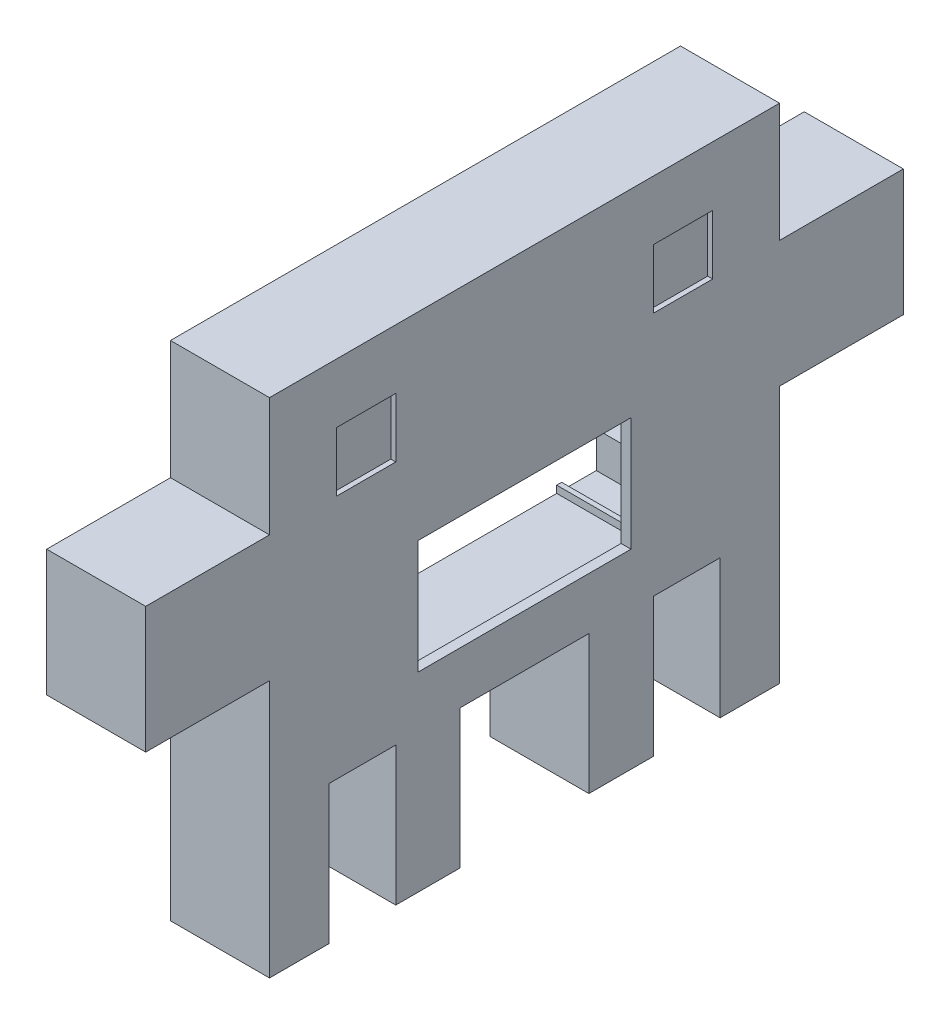
SolidWorks part; units mm, degrees
ref_plane "前视基准面" through (0, 0, 0) normal (0, 0, 1) x (1, 0, 0)
ref_plane "上视基准面" through (0, 0, 0) normal (0, 1, 0) x (1, 0, 0)
ref_plane "右视基准面" through (0, 0, 0) normal (1, 0, 0) x (0, 0, -1)
sketch "草图2" plane through (0, 0, 0) normal (1, 0, 0) x (0, 0, -1)
  line L0 (60.0749, 311.6519) -> (210.0749, 311.6519) construction
  line L1 (109.8601, 259.6877) -> (122.8601, 259.6877)
  line L2 (84.3601, 361.1877) -> (187.3601, 361.1877)
  line L3 (84.3601, 361.1877) -> (84.3601, 337.1877)
  line L4 (84.3601, 259.6877) -> (96.3601, 259.6877)
  line L6 (59.3601, 337.1877) -> (84.3601, 337.1877)
  line L7 (59.3601, 337.1877) -> (59.3601, 311.6877)
  line L8 (59.3601, 311.6877) -> (84.3601, 311.6877)
  line L10 (96.3601, 287.6877) -> (109.8601, 287.6877)
  line L11 (96.3601, 287.6877) -> (96.3601, 259.6877)
  line L13 (109.8601, 287.6877) -> (109.8601, 259.6877)
  line L14 (122.8601, 287.6877) -> (148.8601, 287.6877)
  line L15 (122.8601, 287.6877) -> (122.8601, 259.6877)
  line L25 (84.3601, 311.6877) -> (84.3601, 259.6877)
  line L28 (135.8601, 361.1877) -> (135.8601, 339.1196) construction
  line L33 (97.8601, 349.1877) -> (109.8601, 349.1877)
  line L34 (97.8601, 349.1877) -> (97.8601, 337.1877)
  line L35 (97.8601, 337.1877) -> (109.8601, 337.1877)
  line L36 (109.8601, 349.1877) -> (109.8601, 337.1877)
  line L41 (114.3601, 321.1877) -> (157.3601, 321.1877)
  line L42 (114.3601, 321.1877) -> (114.3601, 298.1877)
  line L43 (114.3601, 298.1877) -> (157.3601, 298.1877)
  line L44 (157.3601, 321.1877) -> (157.3601, 298.1877)
  line L45 (173.8601, 337.1877) -> (161.8601, 337.1877)
  line L46 (173.8601, 349.1877) -> (173.8601, 337.1877)
  line L47 (161.8601, 349.1877) -> (161.8601, 337.1877)
  line L48 (148.8601, 287.6877) -> (148.8601, 259.6877)
  line L49 (161.8601, 259.6877) -> (148.8601, 259.6877)
  line L50 (161.8601, 287.6877) -> (161.8601, 259.6877)
  line L51 (175.3601, 287.6877) -> (161.8601, 287.6877)
  line L52 (175.3601, 287.6877) -> (175.3601, 259.6877)
  line L53 (187.3601, 259.6877) -> (175.3601, 259.6877)
  line L54 (187.3601, 311.6877) -> (187.3601, 259.6877)
  line L55 (212.3601, 311.6877) -> (187.3601, 311.6877)
  line L56 (212.3601, 337.1877) -> (212.3601, 311.6877)
  line L57 (212.3601, 337.1877) -> (187.3601, 337.1877)
  line L58 (187.3601, 361.1877) -> (187.3601, 337.1877)
  line L59 (173.8601, 349.1877) -> (161.8601, 349.1877)
  point P18 (135.8601, 287.6877)
  point P30 (135.8601, 321.1877)
  point P42 (135.8601, 361.1877)
  dimension "D1" = 150
  dimension "D2" = 51.5
  dimension "D3" = 12
  dimension "D4" = 12
  dimension "D5" = 12
  dimension "D6" = 13.5
  dimension "D7" = 24
  dimension "D8" = 25
  dimension "D9" = 25.5
  dimension "D10" = 52
  dimension "D11" = 12
  dimension "D12" = 28
  dimension "D13" = 13.5
  dimension "D14" = 13
  dimension "D15" = 43
  dimension "D16" = 23
  dimension "D18" = 40
extrude "凸台-拉伸1" add sketch "草图2" along normal blind 20
sketch "草图3" plane through (0, 0, 0) normal (-1, 0, 0) x (0, 0, 1)
  line L1 (-178.844, 354.0104) -> (-92.729, 354.0104)
  line L2 (-178.844, 354.0104) -> (-178.844, 334.2849)
  line L3 (-178.844, 334.2849) -> (-92.729, 334.2849)
  line L4 (-92.729, 354.0104) -> (-92.729, 334.2849)
extrude "凸台-拉伸2" add sketch "草图3" against normal blind 19
sketch "草图4" plane through (0, 0, 0) normal (-1, 0, 0) x (0, 0, 1)
  line L0 (-157.3601, 309.6877) -> (-114.3601, 309.6877) construction
  line L1 (-170.3601, 323.9377) -> (-163.3601, 323.9377)
  line L2 (-170.3601, 323.9377) -> (-170.3601, 295.4377)
  line L3 (-170.3601, 295.4377) -> (-163.3601, 295.4377)
  line L4 (-103.3601, 323.9377) -> (-103.3601, 295.4377)
  line L5 (-157.3601, 298.1877) -> (-157.3601, 321.1877) construction
  line L6 (-110.3601, 295.4377) -> (-110.3601, 296.8877)
  line L8 (-111.3601, 323.9377) -> (-111.3601, 322.4877)
  line L9 (-111.3601, 322.4877) -> (-110.3601, 322.4877)
  line L10 (-110.3601, 323.9377) -> (-110.3601, 322.4877)
  line L15 (-111.3601, 296.8877) -> (-110.3601, 296.8877)
  line L16 (-111.3601, 295.4377) -> (-111.3601, 296.8877)
  line L17 (-136.8601, 323.9377) -> (-136.8601, 301.5394) construction
  line L18 (-163.3601, 295.4377) -> (-163.3601, 296.8877)
  line L19 (-162.3601, 296.8877) -> (-163.3601, 296.8877)
  line L20 (-162.3601, 295.4377) -> (-162.3601, 296.8877)
  line L21 (-163.3601, 323.9377) -> (-163.3601, 322.4877)
  line L22 (-162.3601, 322.4877) -> (-163.3601, 322.4877)
  line L23 (-162.3601, 323.9377) -> (-162.3601, 322.4877)
  line L24 (-162.3601, 323.9377) -> (-111.3601, 323.9377)
  line L25 (-162.3601, 295.4377) -> (-111.3601, 295.4377)
  line L26 (-110.3601, 295.4377) -> (-103.3601, 295.4377)
  line L27 (-110.3601, 323.9377) -> (-103.3601, 323.9377)
  point P5 (-135.8601, 309.6877)
  dimension "D2" = 67
  dimension "D3" = 14.25
  dimension "D4" = 13
  dimension "D5" = 7
  dimension "D6" = 1.45
  dimension "D7" = 1
extrude "切除-拉伸1" cut sketch "草图4" against normal blind 18
sketch "草图5" plane through (0, 0, 0) normal (-1, 0, 0) x (0, 0, 1)
  line L1 (-192.3601, 316.6877) -> (-157.3601, 316.6877)
  line L2 (-192.3601, 316.6877) -> (-192.3601, 302.6877)
  line L3 (-192.3601, 302.6877) -> (-184.7322, 302.6877)
  line L4 (-157.3601, 316.6877) -> (-157.3601, 302.6877)
  line L5 (-114.3601, 309.6877) -> (-157.3601, 309.6877) construction
  line L6 (-157.3601, 321.1877) -> (-157.3601, 298.1877) construction
  line L7 (-175.3601, 259.6877) -> (-187.3601, 259.6877) construction
  line L9 (-184.7322, 302.6877) -> (-184.7322, 259.6877)
  line L10 (-184.7322, 259.6877) -> (-177.9608, 259.6877)
  line L11 (-177.9608, 302.6877) -> (-177.9608, 259.6877)
  line L12 (-177.9608, 302.6877) -> (-157.3601, 302.6877)
  point P7 (-157.3601, 309.6877)
  dimension "D1" = 14
  dimension "D2" = 35
  dimension "D3" = 35
extrude "切除-拉伸2" cut sketch "草图5" against normal blind 17
sketch "草图6" plane through (0, 259.6877, 0) normal (0, -1, 0) x (1, 0, 0)
  line L1 (-5.0852, -80.2324) -> (17.171, -80.2324)
  line L2 (-5.0852, -80.2324) -> (-5.0852, -191.8431)
  line L3 (-5.0852, -191.8431) -> (17.171, -191.8431)
  line L4 (17.171, -80.2324) -> (17.171, -191.8431)
